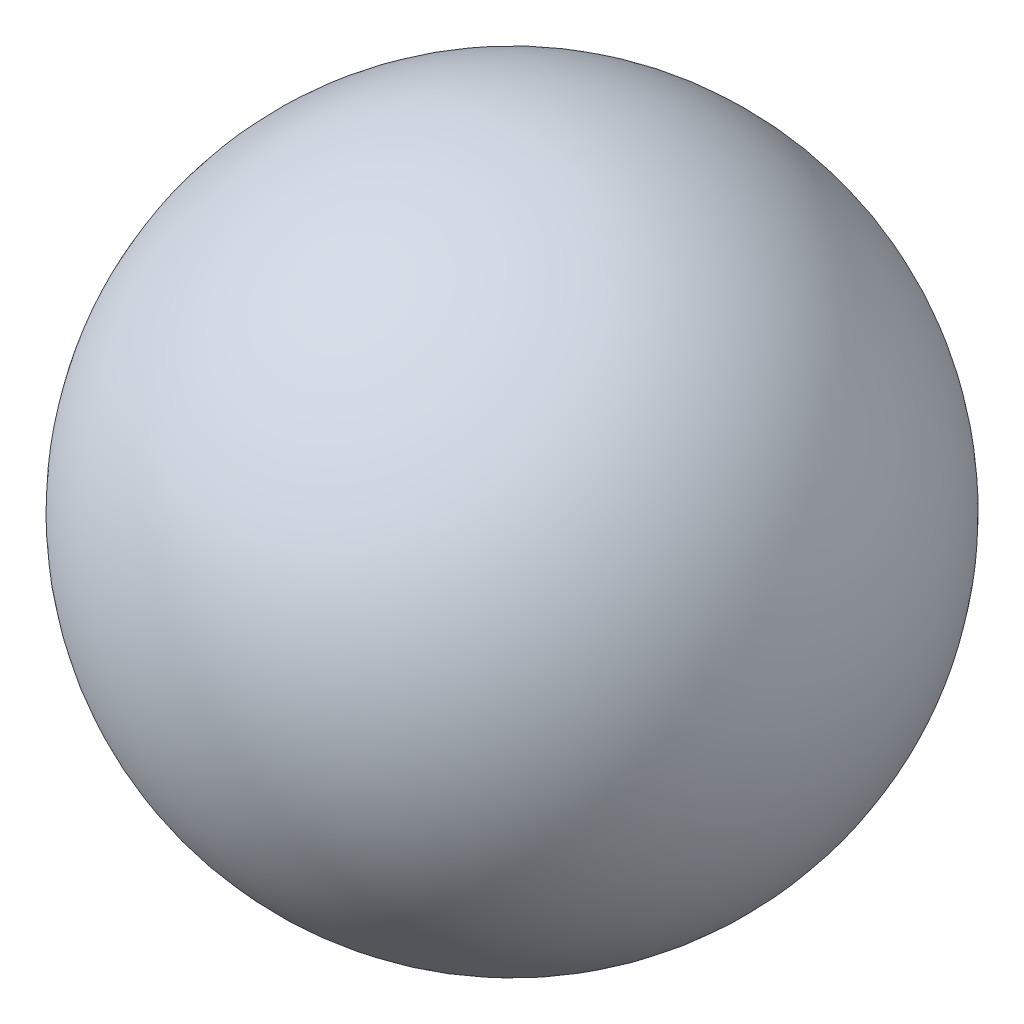
SolidWorks part; units mm, degrees
ref_plane "Front Plane" through (0, 0, 0) normal (0, 0, 1) x (1, 0, 0)
ref_plane "Top Plane" through (0, 0, 0) normal (0, 1, 0) x (1, 0, 0)
ref_plane "Right Plane" through (0, 0, 0) normal (1, 0, 0) x (0, 0, -1)
sketch "Sketch1" plane through (0, 0, 0) normal (0, 0, 1) x (1, 0, 0)
  line L0 (0, 15) -> (0, -15)
  arc A0 (0, -15) -> (0, 15) centre (0, 0) ccw
  dimension "D1" = 15
revolve "Revolve1" add sketch "Sketch1" angle 360 about L0
hole_wizard "M10x1.5 Tapped Hole1" positions "3DSketch1" profile "Sketch2" tap size "M10x1.5" standard "ANSI Metric"
sketch3d "3DSketch1"
  point P0 (-14.9595, -1.101, 0.0008)
sketch "Sketch2" plane through (-14.9595, -1.101, 0.0008) normal (-0.0519, 0.7062, 0.7062) x (0.0519, -0.7042, 0.7081)
  line L0 (0, 0) -> (0, 17.75)
  line L1 (0, 17.75) -> (4.25, 13.5)
  line L2 (4.25, 13.5) -> (4.25, 0)
  line L5 (4.25, 0) -> (0, 0)
  line L10 (0, 17.75) -> (-4.25, 13.5) construction
  line L11 (0, -6.35) -> (0, 107.95) construction
  dimension "Tap Drill Dia." = 8.5
  dimension "Tap Drill Depth" = 13.5
  dimension "Drill Angle" = 90
cosmetic thread "Hole Thread1" parameters "D1"=6, "D2"=10
